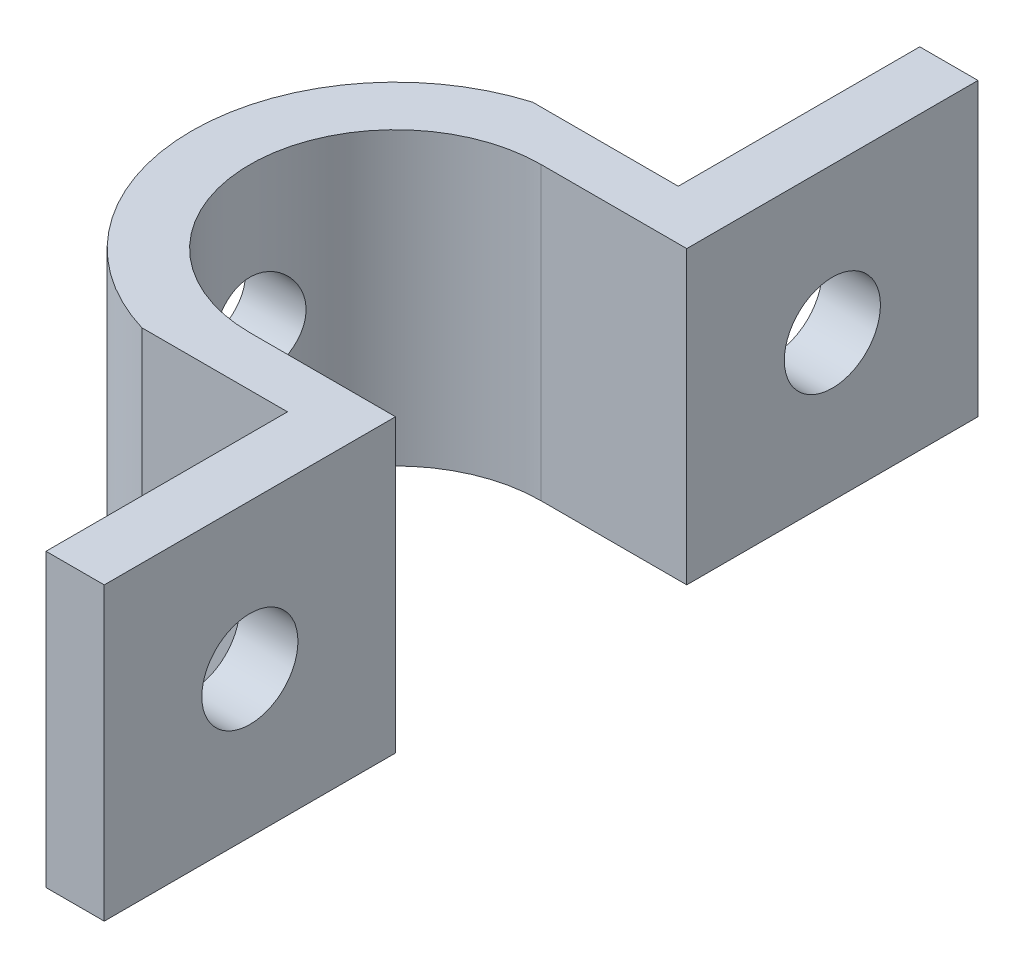
SolidWorks part; units mm, degrees
material "6063-T5"
ref_plane "前视基准面" through (0, 0, 0) normal (0, 0, 1) x (1, 0, 0)
ref_plane "上视基准面" through (0, 0, 0) normal (0, 1, 0) x (1, 0, 0)
ref_plane "右视基准面" through (0, 0, 0) normal (1, 0, 0) x (0, 0, -1)
other "Configuration Table"
sketch "草图1" plane through (0, 0, 0) normal (0, 1, 0) x (1, 0, 0)
  line L0 (0, 0) -> (0, -10)
  line L1 (0, -20) -> (0, -30)
  line L2 (-2, 0) -> (-2, -8.2918)
  line L3 (-2, -21.7082) -> (-2, -30)
  line L4 (-2, 0) -> (0, 0)
  line L5 (-2, -30) -> (0, -30)
  arc A0 (0, -10) -> (0, -20) centre (0, -15) ccw
  arc A1 (-2, -8.2918) -> (-2, -21.7082) centre (0, -15) ccw
  dimension "5" = 5
  dimension "D1" = 10
  dimension "D2" = 10
  dimension "D4" = 2
extrude "凸台-拉伸1" add sketch "草图1" along normal blind 10
ref_plane "基准面3" through (-7, 0, 0) normal (-1, 0, 0) x (0, 0, 1)
sketch "草图11" plane through (-7, 0, 0) normal (-1, 0, 0) x (0, 0, 1)
  line L0 (15, 10) -> (15, 0) construction
  line L1 (21.7082, 10) -> (8.2918, 10) construction
  line L2 (8.2918, 0) -> (21.7082, 0) construction
  line L3 (8.2918, 5) -> (21.7082, 5) construction
  line L4 (8.2918, 10) -> (8.2918, 0) construction
  line L5 (21.7082, 10) -> (21.7082, 0) construction
  point P13 (15, 5)
hole_wizard "M3 螺纹孔的螺纹孔钻头2" positions "草图11" profile "草图14" hole size "M3" standard "GB" end condition through all
sketch "草图14" plane through (-7, 5, 15) normal (0, 1, 0) x (0, 0, 1)
  line L0 (0, 0) -> (0, 7)
  line L1 (0, 7) -> (1.25, 7)
  line L2 (1.25, 7) -> (1.25, 0.025)
  line L3 (1.25, 0.025) -> (1.275, 0)
  line L5 (1.275, 0) -> (0, 0)
  line L6 (-1.25, 0.025) -> (-1.275, 0) construction
  line L11 (0, -6.35) -> (0, 107.95) construction
  dimension "通孔孔直径" = 2.5
  dimension "通孔孔深度" = 7
  dimension "近端锥形沉头孔直径" = 2.55
  dimension "近端锥形沉头孔角度" = 90
sketch "草图15" plane through (0, 0, 0) normal (1, 0, 0) x (0, 0, -1)
  line L4 (-10, 0) -> (0, 0)
  line L5 (0, 0) -> (0, 10)
  line L6 (0, 10) -> (-10, 10)
  line L7 (-10, 10) -> (-10, 0)
  line L8 (-10, 0) -> (0, 0)
  line L9 (0, 0) -> (0, 10)
  line L10 (0, 10) -> (-10, 10)
  line L11 (-10, 10) -> (-10, 0)
  line L12 (-30, 0) -> (-20, 0)
  line L13 (-20, 0) -> (-20, 10)
  line L14 (-20, 10) -> (-30, 10)
  line L15 (-30, 10) -> (-30, 0)
  line L16 (-30, 0) -> (-20, 0)
  line L17 (-20, 0) -> (-20, 10)
  line L18 (-20, 10) -> (-30, 10)
  line L19 (-30, 10) -> (-30, 0)
  dimension "D1" = 0
  dimension "D2" = 0
extrude "凸台-拉伸2" add sketch "草图15" along normal blind 5
sketch "草图16" plane through (5, 0, 0) normal (1, 0, 0) x (0, 0, -1)
  line L0 (-10, 5) -> (0, 5) construction
  line L1 (-10, 10) -> (-10, 0) construction
  line L2 (0, 0) -> (0, 10) construction
  line L3 (-5, 10) -> (-5, 0) construction
  line L4 (0, 10) -> (-10, 10) construction
  line L5 (-10, 0) -> (0, 0) construction
  line L6 (-25, 10) -> (-25, 0) construction
  line L7 (-20, 10) -> (-30, 10) construction
  line L8 (-30, 0) -> (-20, 0) construction
  line L9 (-30, 5) -> (-20, 5) construction
  line L10 (-30, 10) -> (-30, 0) construction
  line L11 (-20, 10) -> (-20, 0) construction
  point P24 (-25, 5)
  point P26 (-5, 5)
hole_wizard "M3 螺纹孔的螺纹孔钻头1" positions "草图16" profile "草图18" hole size "M3" standard "GB" end condition through all
sketch "草图18" plane through (5, 5, 5) normal (0, 1, 0) x (0, 0, -1)
  line L0 (0, 0) -> (0, 12)
  line L1 (0, 12) -> (1.25, 12)
  line L2 (1.25, 12) -> (1.25, 0.025)
  line L3 (1.25, 0.025) -> (1.275, 0)
  line L5 (1.275, 0) -> (0, 0)
  line L6 (-1.25, 0.025) -> (-1.275, 0) construction
  line L11 (0, -6.35) -> (0, 107.95) construction
  dimension "通孔孔直径" = 2.5
  dimension "通孔孔深度" = 12
  dimension "近端锥形沉头孔直径" = 2.55
  dimension "近端锥形沉头孔角度" = 90
sketch "草图19" plane through (-2, 0, 0) normal (-1, 0, 0) x (0, 0, 1)
  line L4 (0, 0) -> (8.2918, 0)
  line L5 (8.2918, 0) -> (8.2918, 10)
  line L6 (8.2918, 10) -> (0, 10)
  line L7 (0, 10) -> (0, 0)
  line L8 (0, 0) -> (8.2918, 0)
  line L9 (8.2918, 0) -> (8.2918, 10)
  line L10 (8.2918, 10) -> (0, 10)
  line L11 (0, 10) -> (0, 0)
  line L12 (21.7082, 0) -> (30, 0)
  line L13 (30, 0) -> (30, 10)
  line L14 (30, 10) -> (21.7082, 10)
  line L15 (21.7082, 10) -> (21.7082, 0)
  line L16 (21.7082, 0) -> (30, 0)
  line L17 (30, 0) -> (30, 10)
  line L18 (30, 10) -> (21.7082, 10)
  line L19 (21.7082, 10) -> (21.7082, 0)
  dimension "D1" = 0
  dimension "D2" = 0
sketch "草图21" plane through (-2, 0, 0) normal (-1, 0, 0) x (0, 0, 1)
  line L4 (0, 0) -> (8.2918, 0)
  line L5 (8.2918, 0) -> (8.2918, 10)
  line L6 (8.2918, 10) -> (0, 10)
  line L7 (0, 10) -> (0, 0)
  line L8 (0, 0) -> (8.2918, 0)
  line L9 (8.2918, 0) -> (8.2918, 10)
  line L10 (8.2918, 10) -> (0, 10)
  line L11 (0, 10) -> (0, 0)
  line L12 (21.7082, 0) -> (30, 0)
  line L13 (30, 0) -> (30, 10)
  line L14 (30, 10) -> (21.7082, 10)
  line L15 (21.7082, 10) -> (21.7082, 0)
  line L16 (21.7082, 0) -> (30, 0)
  line L17 (30, 0) -> (30, 10)
  line L18 (30, 10) -> (21.7082, 10)
  line L19 (21.7082, 10) -> (21.7082, 0)
  dimension "D1" = 0
  dimension "D2" = 0
extrude "切除-拉伸2" cut sketch "草图21" against normal blind 5
sketch "草图23" plane through (3, 0, 0) normal (-1, 0, 0) x (0, 0, 1)
  circle A0 centre (25, 5) radius 1.65
  circle A1 centre (5, 5) radius 1.65
  dimension "D1" = 3.3
  dimension "D2" = 3.3
extrude "切除-拉伸3" cut sketch "草图23" against normal blind 10
sketch "草图24" plane through (-7, 0, 0) normal (-1, 0, 0) x (0, 0, 1)
  circle A0 centre (15, 5) radius 1.65
  dimension "D1" = 3.3
extrude "切除-拉伸4" cut sketch "草图24" against normal blind 10
